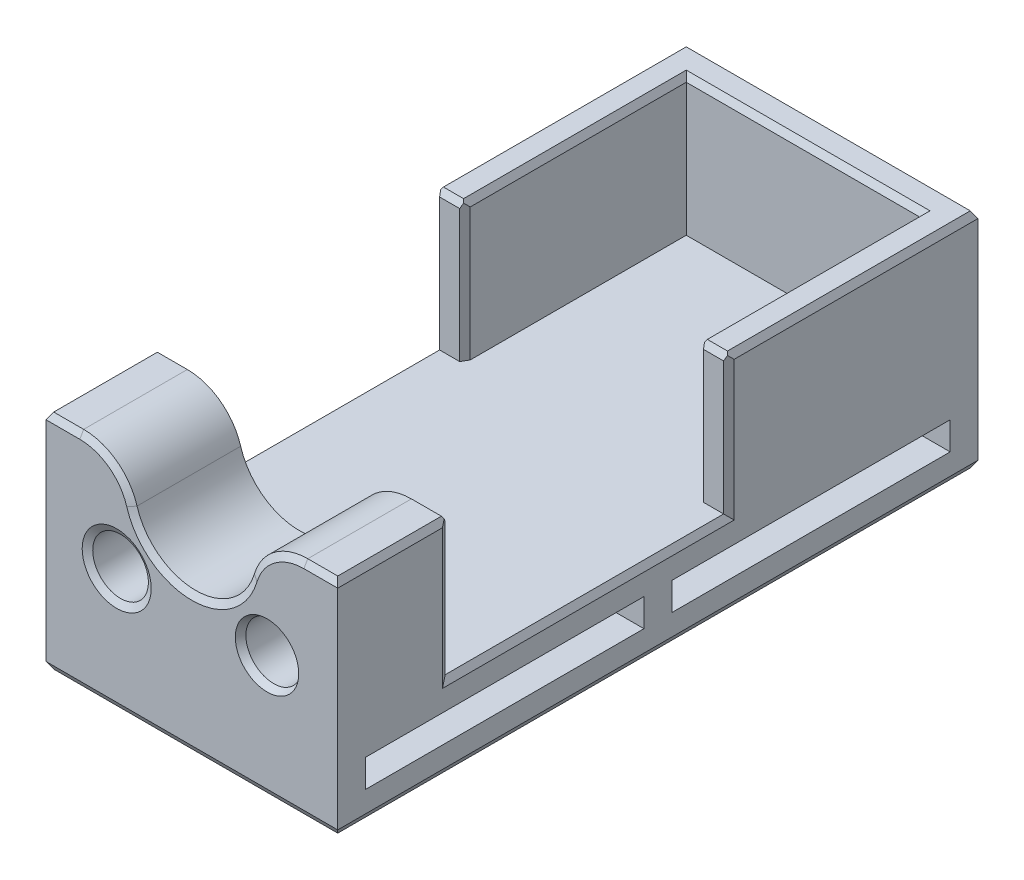
SolidWorks part; units mm, degrees
ref_plane "정면" through (0, 0, 0) normal (0, 0, 1) x (1, 0, 0)
ref_plane "윗면" through (0, 0, 0) normal (0, 1, 0) x (1, 0, 0)
ref_plane "우측면" through (0, 0, 0) normal (1, 0, 0) x (0, 0, -1)
sketch "스케치1" plane through (0, 0, 0) normal (0, 1, 0) x (1, 0, 0)
  line L1 (-26.2, -57.5) -> (26.2, -57.5)
  line L2 (-26.2, -57.5) -> (-26.2, 57.5)
  line L3 (-26.2, 57.5) -> (26.2, 57.5)
  line L4 (26.2, -57.5) -> (26.2, 57.5)
  line L5 (-26.2, -57.5) -> (26.2, 57.5) construction
  line L6 (-26.2, 57.5) -> (26.2, -57.5) construction
  point P0 (0, 0)
  dimension "D1" = 115
  dimension "D2" = 52.4
extrude "보스-돌출1" add sketch "스케치1" along normal mid plane 15
sketch "스케치2" plane through (0, 0, 0) normal (1, 0, 0) x (0, 0, -1)
  line L0 (0, -7.5) -> (0, 7.5) construction
  line L1 (57.5, 7.5) -> (-57.5, 7.5) construction
  line L2 (57.5, -7.5) -> (-57.5, -7.5) construction
  line L3 (-27.5, 0) -> (0, 0) construction
  line L5 (0, 0) -> (27.5, 0) construction
  line L8 (52.5, -2.5) -> (2.5, -2.5)
  line L9 (52.5, -2.5) -> (52.5, 2.5)
  line L10 (52.5, 2.5) -> (2.5, 2.5)
  line L11 (2.5, -2.5) -> (2.5, 2.5)
  line L12 (52.5, -2.5) -> (2.5, 2.5) construction
  line L13 (52.5, 2.5) -> (2.5, -2.5) construction
  line L14 (-2.5, -2.5) -> (-52.5, -2.5)
  line L15 (-2.5, -2.5) -> (-2.5, 2.5)
  line L16 (-2.5, 2.5) -> (-52.5, 2.5)
  line L17 (-52.5, -2.5) -> (-52.5, 2.5)
  line L18 (-2.5, -2.5) -> (-52.5, 2.5) construction
  line L19 (-2.5, 2.5) -> (-52.5, -2.5) construction
  point P5 (27.5, 0)
  point P20 (-27.5, 0)
  dimension "D1" = 50
  dimension "D2" = 5
  dimension "D3" = 5
extrude "컷-돌출1" cut sketch "스케치2" against normal through all both and the other way through all
sketch "스케치3" plane through (0, 0, -57.5) normal (0, 0, -1) x (-1, 0, 0)
  line L1 (-26.2, 7.5) -> (26.2, 7.5)
  line L2 (-26.2, 7.5) -> (-26.2, 32.5)
  line L3 (-26.2, 32.5) -> (26.2, 32.5)
  line L4 (26.2, 7.5) -> (26.2, 32.5)
  dimension "D1" = 25
extrude "보스-돌출2" add sketch "스케치3" against normal blind 5
sketch "스케치4" plane through (0, 0, -52.5) normal (0, 0, 1) x (1, 0, 0)
  line L0 (-26.2, 7.5) -> (26.2, 7.5) construction
  line L1 (-26.2, 32.5) -> (-21.2, 32.5)
  line L2 (-26.2, 32.5) -> (-26.2, 7.5)
  line L3 (-26.2, 7.5) -> (-21.2, 7.5)
  line L4 (-21.2, 32.5) -> (-21.2, 7.5)
  line L6 (26.2, 32.5) -> (21.2, 32.5)
  line L7 (26.2, 32.5) -> (26.2, 7.5)
  line L8 (26.2, 7.5) -> (21.2, 7.5)
  line L9 (21.2, 32.5) -> (21.2, 7.5)
  dimension "D1" = 5
extrude "보스-돌출3" add sketch "스케치4" along normal blind 40
sketch "스케치5" plane through (0, 0, 57.5) normal (0, 0, 1) x (1, 0, 0)
  line L0 (0, 7.5) -> (0, 28.5) construction
  line L1 (-26.2, 7.5) -> (26.2, 7.5) construction
  line L2 (-10.247, 32.5) -> (-26.2, 32.5)
  line L3 (-21.2, 32.5) -> (21.2, 32.5) construction
  line L4 (-26.2, 32.5) -> (-26.2, 7.5)
  line L5 (-26.2, 7.5) -> (26.2, 7.5)
  line L6 (26.2, 7.5) -> (26.2, 32.5)
  line L7 (26.2, 32.5) -> (10.247, 32.5)
  circle A0 centre (0, 28.5) radius 11 construction
  arc A1 (-10.247, 32.5) -> (10.247, 32.5) centre (0, 28.5) ccw
  dimension "D2" = 22
  dimension "D1" = 21
extrude "보스-돌출4" add sketch "스케치5" against normal blind 20
fillet "필렛1" radius 10 2 edges at (10.247, 32.5, 47.5) (-10.247, 32.5, 47.5)
sketch "스케치7" plane through (0, 0, 57.5) normal (0, 0, 1) x (1, 0, 0)
  line L0 (-13.5, 14.5) -> (13.5, 14.5) construction
  line L1 (0, 14.5) -> (0, 0) construction
  circle A0 centre (-13.5, 14.5) radius 5
  circle A1 centre (13.5, 14.5) radius 5
  dimension "D1" = 10
  dimension "D2" = 27
  dimension "D3" = 14.5
extrude "컷-돌출2" cut sketch "스케치7" against normal blind 20
chamfer "모따기1" distance 1.2 angle 30 24 edges at (-23.1623, 32.5, 57.5) (-23.1623, 32.5, 37.5) (-14.1485, 30.5178, 57.5) (-14.1485, 30.5178, 37.5) (0, 17.5, 57.5) (0, 17.5, 37.5) (14.1485, 30.5178, 57.5) (14.1485, 30.5178, 37.5) (23.1623, 32.5, 37.5) (23.1623, 32.5, 57.5) (26.2, 32.5, 47.5) (26.2, 32.5, -35) (23.7, 32.5, -12.5) (21.2, 32.5, -32.5) (0, 32.5, -52.5) (-21.2, 32.5, -32.5) (-23.7, 32.5, -12.5) (-26.2, 32.5, -35) (0, 32.5, -57.5) (0, -7.5, -57.5) (-26.2, -7.5, 0) (0, -7.5, 57.5) (26.2, -7.5, 0) (-26.2, 32.5, 47.5)
chamfer "모따기2" distance 1.2 angle 30 4 edges at (18.5, 14.5, 37.5) (-8.5, 14.5, 37.5) (18.5, 14.5, 57.5) (-8.5, 14.5, 57.5)
chamfer "모따기3" distance 1.2 angle 30 2 edges at (26.2, 7.5, 12.5) (-26.2, 7.5, 12.5)
chamfer "모따기4" distance 1.2 angle 30 6 edges at (26.2, 18.8, 37.5) (-26.2, 18.8, 37.5) (26.2, 18.8, -12.5) (21.2, 19.4, -12.5) (-21.2, 19.4, -12.5) (-26.2, 18.8, -12.5)
